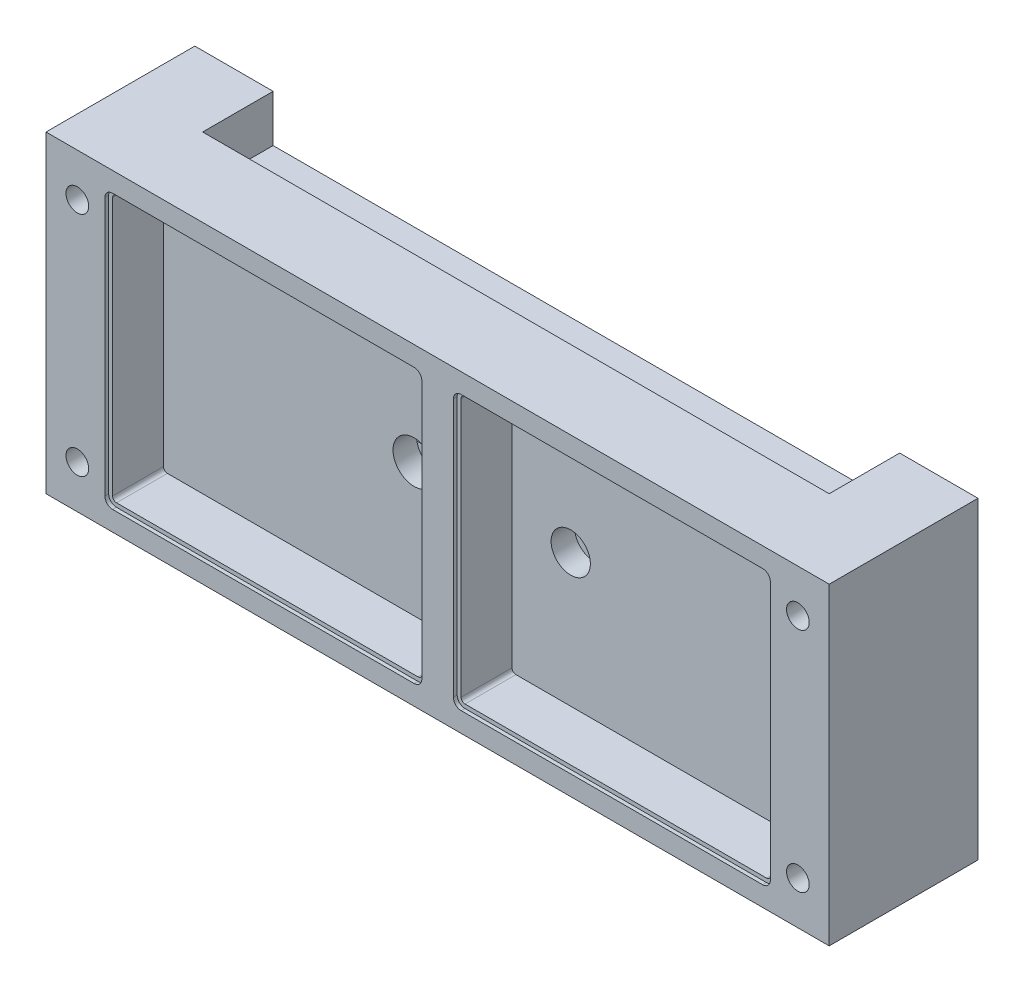
SolidWorks part; units mm, degrees
ref_plane "Front Plane" through (0, 0, 0) normal (0, 0, 1) x (1, 0, 0)
ref_plane "Top Plane" through (0, 0, 0) normal (0, 1, 0) x (1, 0, 0)
ref_plane "Right Plane" through (0, 0, 0) normal (1, 0, 0) x (0, 0, -1)
sketch "Sketch1" plane through (0, 0, 0) normal (0, 0, 1) x (1, 0, 0)
  line L1 (-33.75, 21.5625) -> (66.25, 21.5625)
  line L2 (-33.75, 21.5625) -> (-33.75, -18.4375)
  line L3 (-33.75, -18.4375) -> (66.25, -18.4375)
  line L4 (66.25, 21.5625) -> (66.25, -18.4375)
  dimension "D1" = 100
  dimension "D2" = 40
extrude "Boss-Extrude1" add sketch "Sketch1" along normal blind 38
sketch "Sketch2" plane through (0, 0, 0) normal (0, 0, -1) x (-1, 0, 0)
  line L0 (-66.25, -18.4375) -> (-66.25, 21.5625) construction
  line L1 (-58.25, 18.5625) -> (-18.75, 18.5625)
  line L2 (-58.25, 18.5625) -> (-58.25, -15.4375)
  line L3 (-58.25, -15.4375) -> (-18.75, -15.4375)
  line L4 (-18.75, 18.5625) -> (-18.75, -15.4375)
  line L5 (-13.75, 18.5625) -> (25.75, 18.5625)
  line L6 (-13.75, 18.5625) -> (-13.75, -15.4375)
  line L7 (-13.75, -15.4375) -> (25.75, -15.4375)
  line L8 (25.75, 18.5625) -> (25.75, -15.4375)
  line L9 (33.75, 21.5625) -> (33.75, -18.4375) construction
  line L10 (-66.25, 21.5625) -> (33.75, 21.5625) construction
  line L11 (33.75, -18.4375) -> (-66.25, -18.4375) construction
  dimension "D1" = 8
  dimension "D2" = 8
  dimension "D3" = 5
  dimension "D4" = 3
  dimension "D5" = 3
  dimension "D6" = 3
  dimension "D7" = 3
  dimension "D8" = 39.5
  dimension "D9" = 39.5
extrude "Cut-Extrude2" cut sketch "Sketch2" against normal blind 21 from offset 12 offset against normal yes
sketch "Sketch4" plane through (0, 0, 0) normal (0, 0, -1) x (-1, 0, 0)
  line L0 (-66.25, -18.4375) -> (-66.25, 21.5625) construction
  line L1 (33.75, 21.5625) -> (33.75, -18.4375) construction
  line L2 (-66.25, 21.5625) -> (33.75, 21.5625) construction
  line L3 (33.75, -18.4375) -> (-66.25, -18.4375) construction
  circle A0 centre (-62.25, 16.0625) radius 1.45
  circle A1 centre (-62.25, -12.9375) radius 1.45
  circle A2 centre (29.75, 16.0625) radius 1.45
  circle A3 centre (29.75, -12.9375) radius 1.45
  dimension "D1" = 4
  dimension "D2" = 4
  dimension "D3" = 5.5
  dimension "D4" = 5.5
extrude "Cut-Extrude4" cut sketch "Sketch4" against normal up to next
sketch "Sketch6" plane through (0, 21.5625, 0) normal (0, 1, 0) x (1, 0, 0)
  line L0 (-33.75, -38) -> (-33.75, 0) construction
  line L1 (66.25, -38) -> (-33.75, -38)
  line L2 (66.25, -38) -> (66.25, -19)
  line L3 (66.25, -19) -> (-33.75, -19)
  line L4 (-33.75, -38) -> (-33.75, -19)
extrude "Cut-Extrude5" cut sketch "Sketch6" against normal through all
fillet "Fillet1" radius 0.5 8 edges at (58.25, 18.5625, 15.5) (58.25, -15.4375, 15.5) (18.75, -15.4375, 15.5) (18.75, 18.5625, 15.5) (13.75, 18.5625, 15.5) (13.75, -15.4375, 15.5) (-25.75, -15.4375, 15.5) (-25.75, 18.5625, 15.5)
sketch "Sketch10" plane through (0, 0, 12) normal (0, 0, 1) x (1, 0, 0)
  line L8 (14.25, -14.9375) -> (14.25, 18.0625)
  line L9 (13.25, 19.0625) -> (-25.25, 19.0625)
  line L10 (-26.25, 18.0625) -> (-26.25, -14.9375)
  line L11 (-25.25, -15.9375) -> (13.25, -15.9375)
  line L12 (14.25, -14.9375) -> (14.25, 18.0625)
  line L13 (13.25, 19.0625) -> (-25.25, 19.0625)
  line L14 (-26.25, 18.0625) -> (-26.25, -14.9375)
  line L15 (-25.25, -15.9375) -> (13.25, -15.9375)
  arc A8 (14.25, 18.0625) -> (13.25, 19.0625) centre (13.25, 18.0625) ccw
  arc A9 (-25.25, 19.0625) -> (-26.25, 18.0625) centre (-25.25, 18.0625) ccw
  arc A10 (-26.25, -14.9375) -> (-25.25, -15.9375) centre (-25.25, -14.9375) ccw
  arc A11 (13.25, -15.9375) -> (14.25, -14.9375) centre (13.25, -14.9375) ccw
  arc A12 (14.25, 18.0625) -> (13.25, 19.0625) centre (13.25, 18.0625) ccw
  arc A13 (-25.25, 19.0625) -> (-26.25, 18.0625) centre (-25.25, 18.0625) ccw
  arc A14 (-26.25, -14.9375) -> (-25.25, -15.9375) centre (-25.25, -14.9375) ccw
  arc A15 (13.25, -15.9375) -> (14.25, -14.9375) centre (13.25, -14.9375) ccw
  dimension "D1" = 0.5
extrude "Cut-Extrude6" cut sketch "Sketch10" along normal blind 0.5 draft 2 from offset 6.5
sketch "Sketch11" plane through (0, 0, 12) normal (0, 0, 1) x (1, 0, 0)
  line L8 (58.75, -14.9375) -> (58.75, 18.0625)
  line L9 (57.75, 19.0625) -> (19.25, 19.0625)
  line L10 (18.25, 18.0625) -> (18.25, -14.9375)
  line L11 (19.25, -15.9375) -> (57.75, -15.9375)
  line L12 (58.75, -14.9375) -> (58.75, 18.0625)
  line L13 (57.75, 19.0625) -> (19.25, 19.0625)
  line L14 (18.25, 18.0625) -> (18.25, -14.9375)
  line L15 (19.25, -15.9375) -> (57.75, -15.9375)
  arc A8 (58.75, 18.0625) -> (57.75, 19.0625) centre (57.75, 18.0625) ccw
  arc A9 (19.25, 19.0625) -> (18.25, 18.0625) centre (19.25, 18.0625) ccw
  arc A10 (18.25, -14.9375) -> (19.25, -15.9375) centre (19.25, -14.9375) ccw
  arc A11 (57.75, -15.9375) -> (58.75, -14.9375) centre (57.75, -14.9375) ccw
  arc A12 (58.75, 18.0625) -> (57.75, 19.0625) centre (57.75, 18.0625) ccw
  arc A13 (19.25, 19.0625) -> (18.25, 18.0625) centre (19.25, 18.0625) ccw
  arc A14 (18.25, -14.9375) -> (19.25, -15.9375) centre (19.25, -14.9375) ccw
  arc A15 (57.75, -15.9375) -> (58.75, -14.9375) centre (57.75, -14.9375) ccw
  dimension "D1" = 0.5
extrude "Cut-Extrude7" cut sketch "Sketch11" along normal blind 0.5 draft 2 from offset 6.5
sketch "Sketch17" plane through (0, 0, 0) normal (0, 0, -1) x (-1, 0, 0)
  line L0 (-66.25, 1.5625) -> (33.75, 1.5625) construction
  line L3 (-16.25, 21.5625) -> (-16.25, -18.4375) construction
  line L4 (-66.25, 21.5625) -> (33.75, 21.5625) construction
  line L5 (33.75, -18.4375) -> (-66.25, -18.4375) construction
  line L6 (-66.25, -18.4375) -> (-66.25, 21.5625) construction
  line L9 (33.75, 21.5625) -> (33.75, -18.4375) construction
  line L10 (-56.25, 1.5625) -> (23.75, 1.5625) construction
  line L11 (-56.25, 9.0625) -> (23.75, 9.0625)
  line L12 (-56.25, -5.9375) -> (23.75, -5.9375)
  arc A2 (-56.25, 9.0625) -> (-56.25, -5.9375) centre (-56.25, 1.5625) ccw
  arc A3 (23.75, -5.9375) -> (23.75, 9.0625) centre (23.75, 1.5625) ccw
  point P15 (-16.25, 1.5625)
extrude "Cut-Extrude12" cut sketch "Sketch17" against normal blind 9
sketch "Sketch18" plane through (0, 0, 9) normal (0, 0, -1) x (-1, 0, 0)
  line L0 (-66.25, 1.5625) -> (33.75, 1.5625) construction
  line L1 (-66.25, -18.4375) -> (-66.25, 21.5625) construction
  line L2 (33.75, 21.5625) -> (33.75, -18.4375) construction
  line L3 (-16.25, 21.5625) -> (-16.25, -18.4375) construction
  line L4 (-66.25, 21.5625) -> (33.75, 21.5625) construction
  line L5 (33.75, -18.4375) -> (-66.25, -18.4375) construction
  circle A0 centre (-26.25, 1.5625) radius 2.5069
  circle A1 centre (-6.25, 1.5625) radius 2.6931
  dimension "D1" = 20
  dimension "D2" = 10
  dimension "D3" = 10
extrude "Cut-Extrude13" cut sketch "Sketch18" against normal up to next
sketch "Sketch19" plane through (0, 0, 9) normal (0, 0, -1) x (-1, 0, 0)
  circle A0 centre (-26.25, 1.5625) radius 4.572
  circle A1 centre (-26.25, 1.5625) radius 6.477
  circle A2 centre (-6.25, 1.5625) radius 4.572
  circle A3 centre (-6.25, 1.5625) radius 6.477
  dimension "D1" = 9.144
  dimension "D2" = 12.954
  dimension "D3" = 12.954
  dimension "D4" = 9.144
extrude "Cut-Extrude14" cut sketch "Sketch19" against normal blind 0.7937 contours A1 A0 | A3 A2
sketch "Sketch20" plane through (-33.75, 0, 0) normal (-1, 0, 0) x (0, 0, 1)
  line L0 (0, 12.0625) -> (-2, 12.0625)
  line L1 (0, 21.5625) -> (0, -18.4375) construction
  line L2 (-2, 12.0625) -> (-2, 9.0625)
  line L8 (9, 9.0625) -> (9, -5.9375) construction
  line L9 (9, 1.5625) -> (-12.0371, 1.5625) construction
  line L10 (-2, -8.9375) -> (-2, -5.9375)
  line L15 (0, -8.9375) -> (-2, -8.9375)
  line L16 (-2, 9.0625) -> (0, 9.0625)
  line L17 (0, 9.0625) -> (0, 12.0625)
  line L18 (-2, -5.9375) -> (0, -5.9375)
  line L19 (0, -5.9375) -> (0, -8.9375)
  dimension "D4" = 3
  dimension "D5" = 2
sketch "Sketch21" plane through (0, 0, 0) normal (0, 0, -1) x (-1, 0, 0)
  line L0 (33.75, 21.5625) -> (33.75, -18.4375) construction
  line L1 (23.75, 9.0625) -> (33.75, 9.0625)
  line L2 (23.75, 9.0625) -> (23.75, -5.9375)
  line L3 (23.75, -5.9375) -> (33.75, -5.9375)
  line L4 (33.75, 9.0625) -> (33.75, -5.9375)
extrude "Cut-Extrude15" cut sketch "Sketch21" against normal up to surface (9 mm away) up to face at (19.773, 1.5625, 9)
sketch "Sketch22" plane through (-33.75, 0, 0) normal (-1, 0, 0) x (0, 0, 1)
  line L0 (9, 1.5625) -> (-10.0634, 1.5625) construction
  line L1 (9, 9.0625) -> (9, -5.9375) construction
  line L2 (9, 9.0625) -> (0, 9.0625) construction
  line L3 (2, 9.0625) -> (6, 9.0625)
  line L4 (2, 9.0625) -> (2, 11.5625)
  line L5 (2, 11.5625) -> (6, 11.5625)
  line L6 (6, 9.0625) -> (6, 11.5625)
  line L7 (2, -5.9375) -> (2, -8.4375)
  line L8 (2, -5.9375) -> (6, -5.9375)
  line L9 (6, -5.9375) -> (6, -8.4375)
  line L10 (2, -8.4375) -> (6, -8.4375)
  line L11 (0, 21.5625) -> (0, 9.0625) construction
  dimension "D1" = 4
  dimension "D2" = 2.5
  dimension "D3" = 2
extrude "Cut-Extrude16" cut sketch "Sketch22" against normal blind 90
sketch "Sketch23" plane through (0, 0, 0) normal (0, 0, -1) x (-1, 0, 0)
  line L0 (-63.75, 1.5625) -> (37.5576, 1.5625) construction
  line L1 (-66.25, 21.5625) -> (33.75, 21.5625) construction
  line L2 (-56.25, 21.5625) -> (23.75, 21.5625)
  line L3 (-56.25, 21.5625) -> (-56.25, 15.5625)
  line L4 (-56.25, 15.5625) -> (23.75, 15.5625)
  line L5 (23.75, 21.5625) -> (23.75, 15.5625)
  line L6 (-56.25, -18.4375) -> (-56.25, -12.4375)
  line L7 (-56.25, -18.4375) -> (23.75, -18.4375)
  line L8 (23.75, -18.4375) -> (23.75, -12.4375)
  line L9 (-56.25, -12.4375) -> (23.75, -12.4375)
  line L10 (33.75, 21.5625) -> (33.75, 9.0625) construction
  arc A0 (-56.25, 9.0625) -> (-56.25, -5.9375) centre (-56.25, 1.5625) ccw construction
  dimension "D1" = 80
  dimension "D2" = 10
  dimension "D3" = 6
extrude "Cut-Extrude17" cut sketch "Sketch23" against normal blind 9
